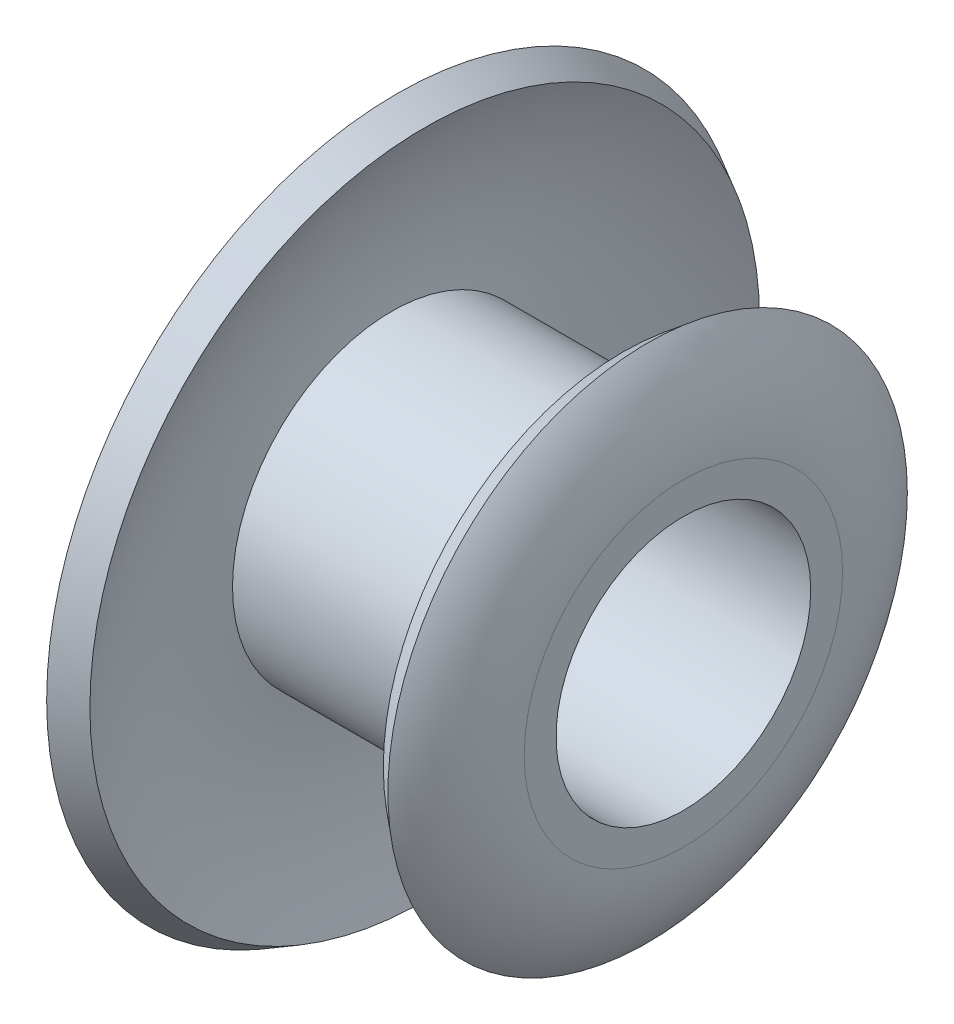
SolidWorks part; units mm, degrees
ref_plane "Front Plane" through (0, 0, 0) normal (0, 0, 1) x (1, 0, 0)
ref_plane "Top Plane" through (0, 0, 0) normal (0, 1, 0) x (1, 0, 0)
ref_plane "Right Plane" through (0, 0, 0) normal (1, 0, 0) x (0, 0, -1)
sketch "Sketch1" plane through (0, 0, 0) normal (0, 0, 1) x (1, 0, 0)
  line L0 (0, 0) -> (-2.433, 0) construction
  line L1 (-2.0406, 1.25) -> (0, 1.25)
  line L2 (-2, 1) -> (0, 1)
  line L3 (0, 1) -> (0.25, 1)
  line L4 (-2, 1) -> (-2.25, 1)
  line L5 (-2, 2.75) -> (-1.781, 2.6294)
  line L6 (-2, 1.25) -> (0, 1.25) construction
  line L7 (0.25, 1) -> (0.25, 1.25)
  line L8 (-0.2248, 1.8817) -> (-0.031, 2.0396)
  arc A0 (-2.25, 1) -> (-2, 2.75) centre (0.19, 1.5443) cw
  arc A1 (-2.0406, 1.25) -> (-1.781, 2.6294) centre (0.19, 1.5443) cw
  arc A2 (-2.006, 1.0544) -> (-1.781, 2.6294) centre (0.19, 1.5443) cw construction
  arc A3 (0.25, 1.25) -> (-0.031, 2.0396) centre (-1, 1.25) ccw
  arc A4 (0, 1.25) -> (-0.2248, 1.8817) centre (-1, 1.25) ccw
  dimension "D6" = 2.5
  dimension "D7" = 1.5
  dimension "D10" = 1.25
  dimension "D1" = 2.5
  dimension "D2" = 2.0406
  dimension "D4" = 0.25
  dimension "D5" = 0.25
  dimension "D9" = 0.0406
  dimension "D11" = 1.75
  dimension "D3" = 0.25
  dimension "D8" = 0.25
  dimension "D12" = 0.25
revolve "Revolve1" add sketch "Sketch1" angle 360 about L0
fillet "Fillet1" [suppressed] radius 0.1
